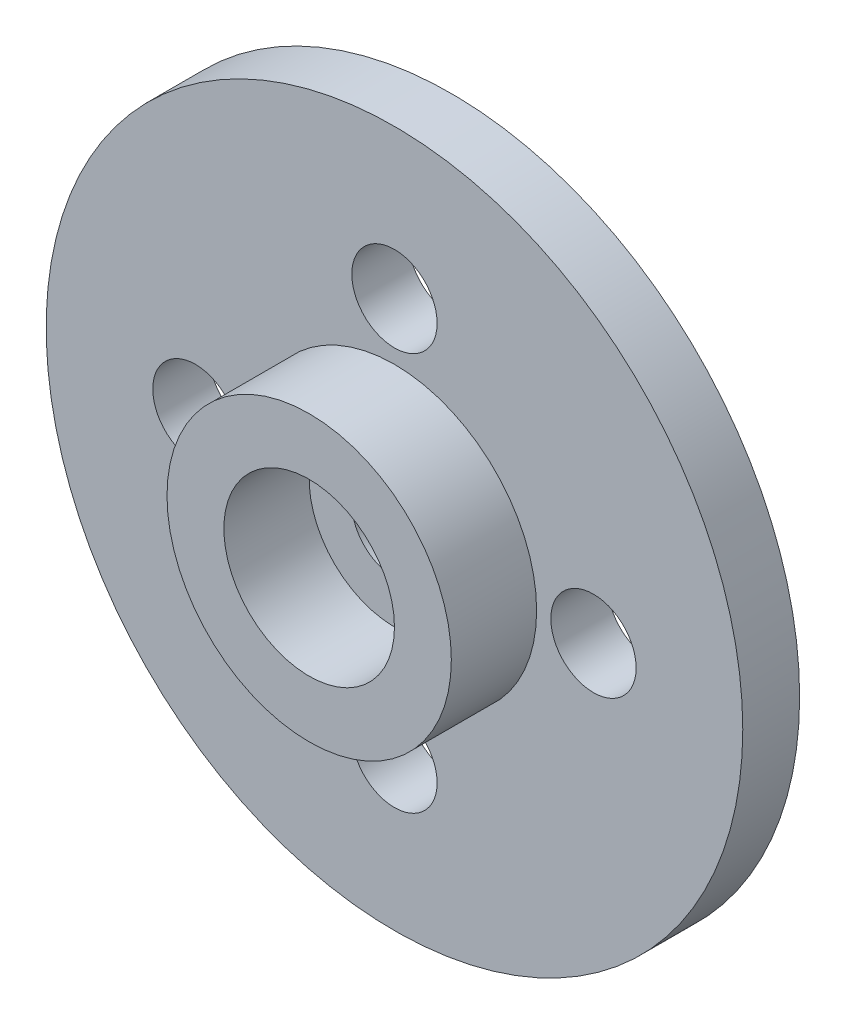
SolidWorks part; units mm, degrees
material "6061 合金"
ref_plane "前视基准面" through (0, 0, 0) normal (0, 0, 1) x (1, 0, 0)
ref_plane "上视基准面" through (0, 0, 0) normal (0, 1, 0) x (1, 0, 0)
ref_plane "右视基准面" through (0, 0, 0) normal (1, 0, 0) x (0, 0, -1)
sketch "草图1" plane through (0, 0, 0) normal (0, 0, 1) x (1, 0, 0)
  circle A0 centre (0, 0) radius 1.5
  circle A1 centre (0, 0) radius 12.25
  dimension "D1" = 3
  dimension "D2" = 24.5
extrude "凸台-拉伸1" add sketch "草图1" along normal blind 2
sketch "草图2" plane through (0, 0, 2) normal (0, 0, 1) x (1, 0, 0)
  circle A0 centre (0, 0) radius 5
  circle A1 centre (0, 0) radius 3
  dimension "D1" = 6
  dimension "D2" = 10
extrude "凸台-拉伸2" add sketch "草图2" along normal blind 3
sketch "草图3" plane through (0, 0, 0) normal (0, 0, -1) x (-1, 0, 0)
  line L0 (0, 0) -> (0, 15) construction
  line L1 (-12.0306, -2.3082) -> (-4.9104, -39.4188)
  line L2 (12.0306, -2.3082) -> (4.9104, -39.4188)
  line L3 (-7.5, -38.4766) -> (7.5, -38.4766)
  line L4 (-12.0306, -2.3082) -> (12.0306, -2.3082)
  arc A1 (-7.5, -38.4766) -> (7.5, -38.4766) centre (0, 15) ccw
  circle A2 centre (0, -38.4766) radius 5
  circle A3 centre (0, 0) radius 12.25 construction
  circle M1 centre (0, 0) radius 12.25
  dimension "D2" = 54
  dimension "D3" = 15
  dimension "D4" = 10
  dimension "D1" = 15
extrude "凸台-拉伸3" add sketch "草图3" against normal blind 2 contours A2 L3 L2 L1 M1 | L3 A2 | L3 A2 A1 | A1 A2 | A2 A1 L2 L3 | A2 L2 A1 | A2 L3 L1 A1 | A2 A1 L1
sketch "草图4" plane through (0, 0, 0) normal (0, 0, -1) x (-1, 0, 0)
  line L0 (7, 0) -> (0, 0) construction
  circle A0 centre (7, 0) radius 1.5
  circle A1 centre (0, -7) radius 1.5
  circle A2 centre (-7, 0) radius 1.5
  circle A3 centre (0, 7) radius 1.5
  point P13 (0, 0)
  dimension "D1" = 3
  dimension "D2" = 7
  dimension "D3" = 4
extrude "切除-拉伸1" cut sketch "草图4" against normal blind 10
sketch "草图5" [suppressed] plane through (0, 0, 5) normal (0, 0, 1) x (1, 0, 0)
  circle A0 centre (0, 0) radius 5
extrude "切除-拉伸2" [suppressed] cut sketch "草图5" against normal blind 3
sketch "草图6" plane through (0, 0, 2) normal (0, 0, 1) x (1, 0, 0)
  line L0 (-12.25, 0) -> (-14.8569, -46.4247)
  line L1 (-14.8569, -46.4247) -> (15.08, -43.0933)
  line L2 (15.08, -43.0933) -> (12.25, 0)
  circle A0 centre (0, 0) radius 12.25
  line M8 (-12.0306, -2.3082) -> (-4.9104, -39.4188)
  arc M9 (-4.9104, -39.4188) -> (4.9104, -39.4188) centre (0, -38.4766) ccw
  line M10 (4.9104, -39.4188) -> (12.0306, -2.3082)
extrude "切除-拉伸4" cut sketch "草图6" against normal blind 10 contours A0 M8 M9 M10 | L0 L1 L2
sketch "草图7" [suppressed] plane through (0, 0, 2) normal (0, 0, 1) x (1, 0, 0)
  line L2 (-12.0053, -2.4361) -> (-4.9001, -37.4506)
  line L3 (4.9001, -37.4506) -> (12.0053, -2.4361)
  line L4 (-12.0053, -2.4361) -> (-4.9001, -37.4506)
  line L5 (4.9001, -37.4506) -> (12.0053, -2.4361)
  circle A0 centre (7, 0) radius 1.5 construction
  circle A1 centre (0, -7) radius 1.5 construction
  arc A2 (12.0053, -2.4361) -> (-12.0053, -2.4361) centre (0, 0) ccw
  arc A3 (-4.9001, -37.4506) -> (4.9001, -37.4506) centre (0, -36.4563) ccw
  arc A4 (12.0053, -2.4361) -> (-12.0053, -2.4361) centre (0, 0) ccw
  arc A5 (-4.9001, -37.4506) -> (4.9001, -37.4506) centre (0, -36.4563) ccw
  circle A6 centre (-7, 0) radius 1.5 construction
  circle A7 centre (0, 7) radius 1.5 construction
  circle A8 centre (7, 0) radius 1.5
  circle A9 centre (0, -7) radius 1.5
  circle A10 centre (-7, 0) radius 1.5
  circle A11 centre (0, 7) radius 1.5
  dimension "D1" = 0
extrude "凸台-拉伸4" [suppressed] add sketch "草图7" along normal blind 7
